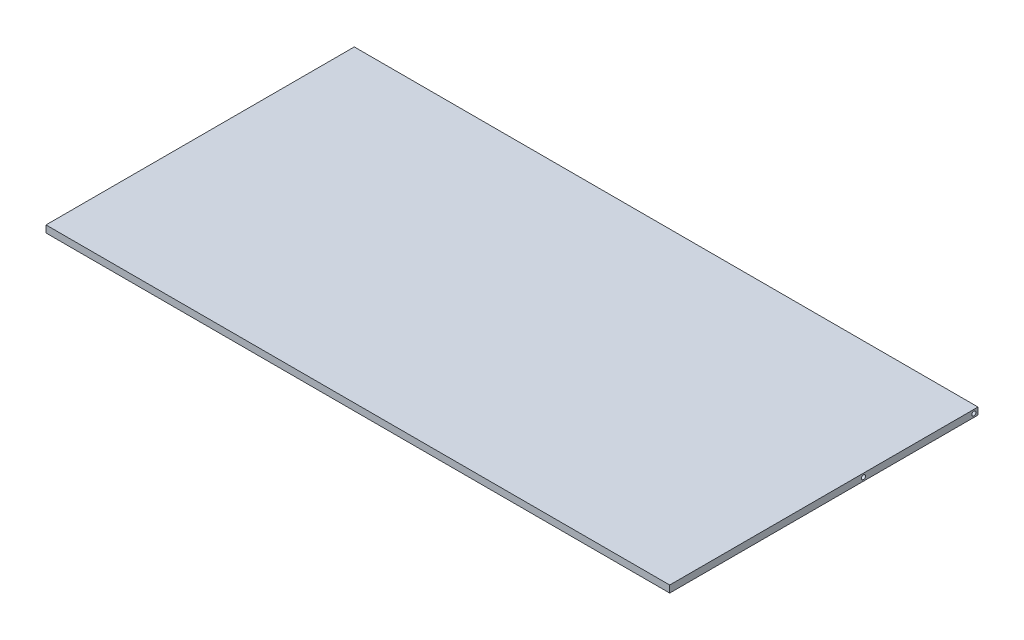
SolidWorks part; units mm, degrees
ref_plane "Front Plane" through (0, 0, 0) normal (0, 0, 1) x (1, 0, 0)
ref_plane "Top Plane" through (0, 0, 0) normal (0, 1, 0) x (1, 0, 0)
ref_plane "Right Plane" through (0, 0, 0) normal (1, 0, 0) x (0, 0, -1)
sketch "Sketch1" plane through (0, 0, 0) normal (0, 1, 0) x (1, 0, 0)
  line L1 (0, 0) -> (1130.4706, 0)
  line L2 (0, 0) -> (0, 558.8)
  line L3 (0, 558.8) -> (1130.4706, 558.8)
  line L4 (1130.4706, 0) -> (1130.4706, 558.8)
  dimension "D1" = 558.8
extrude "Boss-Extrude1" add sketch "Sketch1" along normal blind 12.7
sketch "Sketch2" plane through (1130.4706, 0, 0) normal (1, 0, 0) x (0, 0, -1)
  line L0 (558.8, 12.7) -> (558.8, 0) construction
  circle A0 centre (551.3, 6.35) radius 3.75
  circle A1 centre (351.3, 6.35) radius 3.75
  point P4 (0, 0)
  point P7 (0, 0)
  point P8 (558.8, 6.35)
  dimension "D1" = 7.5
  dimension "D2" = 7.5
  dimension "D3" = 200
extrude "Cut-Extrude1" cut sketch "Sketch2" against normal blind 10
